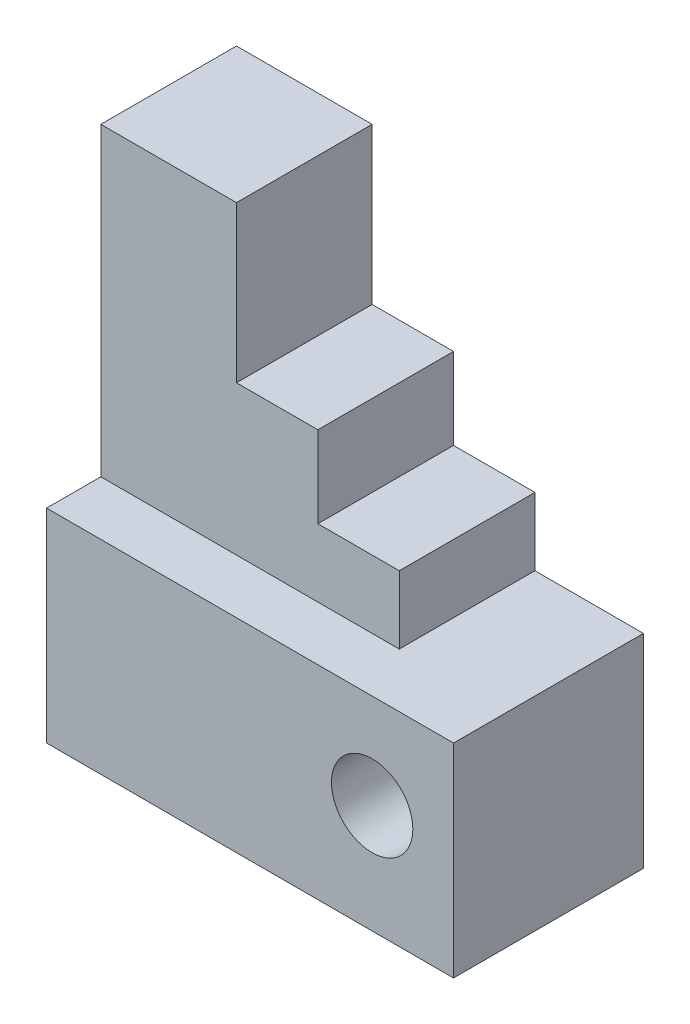
SolidWorks part; units mm, degrees
ref_plane "Front Plane" through (0, 0, 0) normal (0, 0, 1) x (1, 0, 0)
ref_plane "Top Plane" through (0, 0, 0) normal (0, 1, 0) x (1, 0, 0)
ref_plane "Right Plane" through (0, 0, 0) normal (1, 0, 0) x (0, 0, -1)
sketch "Sketch1" plane through (0, 0, 0) normal (0, 0, 1) x (1, 0, 0)
  line L0 (0, 30) -> (0, 75)
  line L1 (0, 0) -> (60, 0)
  line L2 (0, 0) -> (0, 30)
  line L3 (0, 30) -> (60, 30)
  line L4 (60, 0) -> (60, 30)
  line L5 (0, 75) -> (20, 75)
  line L6 (20, 75) -> (20, 52)
  line L7 (20, 52) -> (32, 52)
  line L8 (32, 52) -> (32, 40)
  line L9 (32, 40) -> (44, 40)
  line L10 (44, 40) -> (44, 30)
  circle A0 centre (48, 16) radius 6
  dimension "D3" = 12
  dimension "D1" = 60
  dimension "D2" = 30
  dimension "D4" = 14
  dimension "D5" = 48
  dimension "D6" = 75
  dimension "D7" = 52
  dimension "D8" = 40
  dimension "D9" = 20
  dimension "D10" = 32
  dimension "D11" = 44
extrude "Boss-Extrude5" add sketch "Sketch1" along normal blind 28 contours L1 L4 L3 L2 A0
sketch "Sketch7" plane through (0, 0, 0) normal (0, 0, 1) x (1, 0, 0)
  line L0 (44, 30) -> (0, 30)
  line L1 (0, 30) -> (0, 75)
  line L2 (0, 75) -> (20, 75)
  line L3 (20, 75) -> (20, 52)
  line L4 (20, 52) -> (32, 52)
  line L5 (32, 52) -> (32, 40)
  line L6 (32, 40) -> (44, 40)
  line L7 (44, 40) -> (44, 30)
extrude "Boss-Extrude6" add sketch "Sketch7" along normal blind 20
